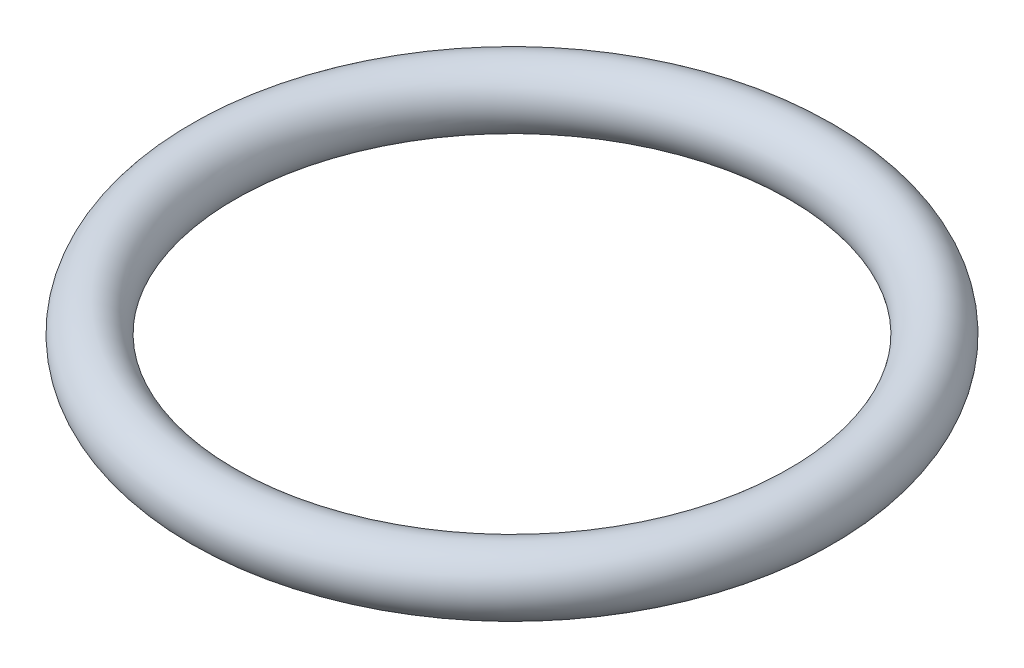
SolidWorks part; units mm, degrees
ref_plane "Front Plane" through (0, 0, 0) normal (0, 0, 1) x (1, 0, 0)
ref_plane "Top Plane" through (0, 0, 0) normal (0, 1, 0) x (1, 0, 0)
ref_plane "Right Plane" through (0, 0, 0) normal (1, 0, 0) x (0, 0, -1)
sketch "Sketch1" plane through (0, 0, 0) normal (0, 0, 1) x (1, 0, 0)
  line L0 (0, 0) -> (-4.85, 0) construction
  line L1 (0, 0) -> (0, 5.4622) construction
  circle A0 centre (-4.85, 0) radius 0.5
  dimension "D2" = 1
  dimension "D1" = 4.85
revolve "Revolve1" add sketch "Sketch1" angle 360 about L1
